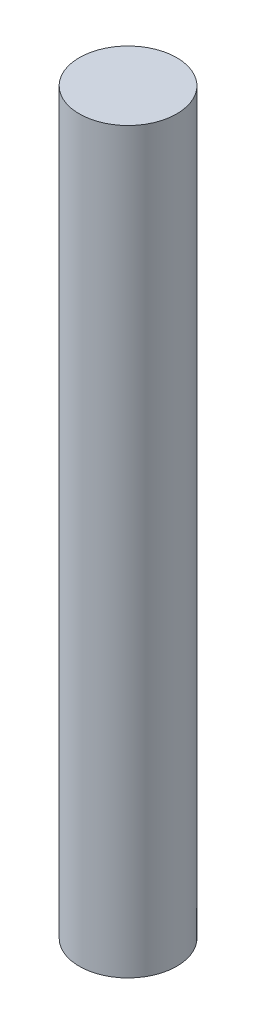
SolidWorks part; units mm, degrees
ref_plane "Front Plane" through (0, 0, 0) normal (0, 0, 1) x (1, 0, 0)
ref_plane "Top Plane" through (0, 0, 0) normal (0, 1, 0) x (1, 0, 0)
ref_plane "Right Plane" through (0, 0, 0) normal (1, 0, 0) x (0, 0, -1)
sketch "Sketch1" plane through (0, 0, 0) normal (0, 1, 0) x (1, 0, 0)
  circle A0 centre (0, 0) radius 3.175
  dimension "D1" = 6.35
extrude "Boss-Extrude1" add sketch "Sketch1" along normal blind 48.1
